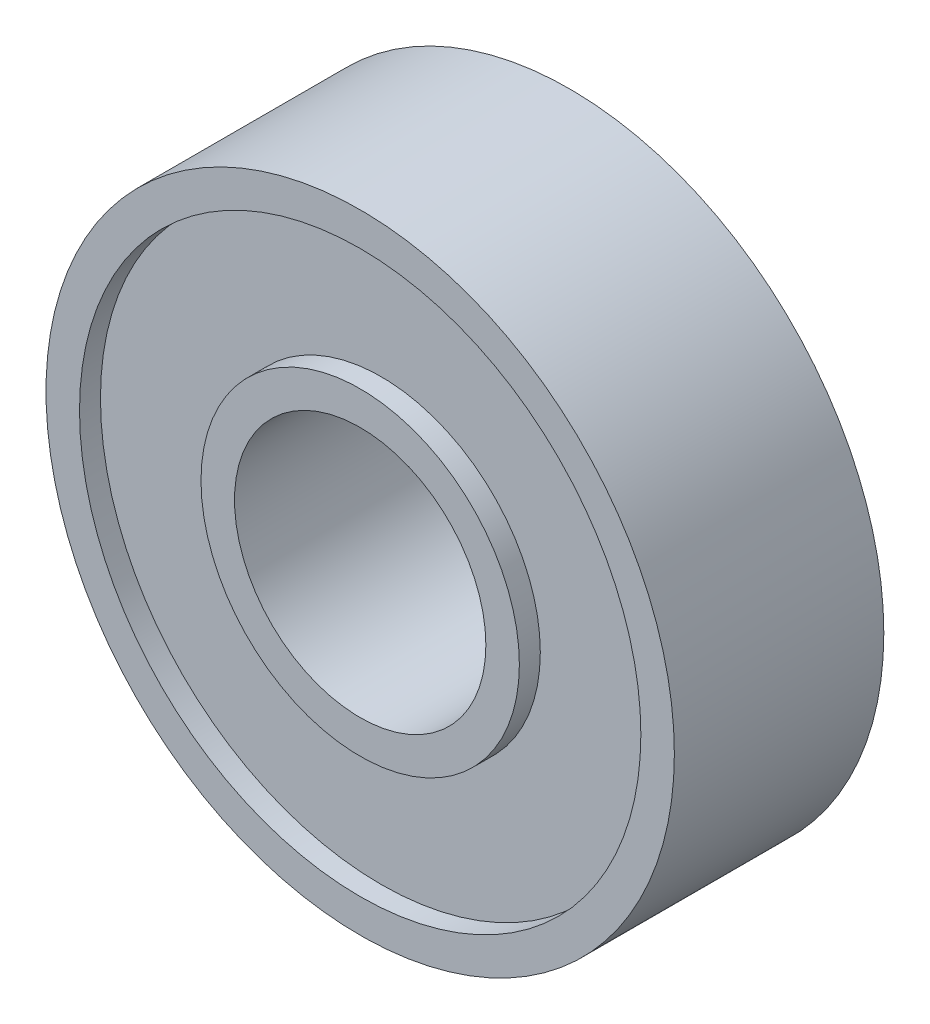
SolidWorks part; units mm, degrees
material "ｽﾃﾝﾚｽ鋼(ｸﾛﾑ)"
ref_plane "正面" through (0, 0, 0) normal (0, 0, 1) x (1, 0, 0)
ref_plane "平面" through (0, 0, 0) normal (0, 1, 0) x (1, 0, 0)
ref_plane "右側面" through (0, 0, 0) normal (1, 0, 0) x (0, 0, -1)
sketch "ｽｹｯﾁ1" plane through (0, 0, 0) normal (1, 0, 0) x (0, 0, -1)
  line L0 (0, 0) -> (50000, 0) construction
  line L1 (0, 0) -> (0, -50000) construction
  line L2 (2.5, 7.5) -> (-2.5, 7.5)
  line L3 (-2.5, 7.5) -> (-2.5, 6.7)
  line L4 (-2.5, 6.7) -> (-2, 6.7)
  line L5 (-2, 6.7) -> (-2, 3.8)
  line L6 (-2, 3.8) -> (-2.5, 3.8)
  line L7 (-2.5, 3.8) -> (-2.5, 3)
  line L8 (-2.5, 3) -> (2.5, 3)
  line L9 (2, 6.7) -> (2, 3.8)
  line L10 (2.5, 3.8) -> (2.5, 3)
  line L11 (2, 3.8) -> (2.5, 3.8)
  line L12 (2.5, 6.7) -> (2, 6.7)
  line L13 (2.5, 7.5) -> (2.5, 6.7)
  point P16 (0, 3)
  point P19 (0, 7.5)
  dimension "D1" = 6
  dimension "D2" = 7.6
  dimension "D3" = 13.4
  dimension "D4" = 15
  dimension "D5" = 0.5
  dimension "D6" = 5
revolve "回転1" add sketch "ｽｹｯﾁ1" angle 360 about L0
